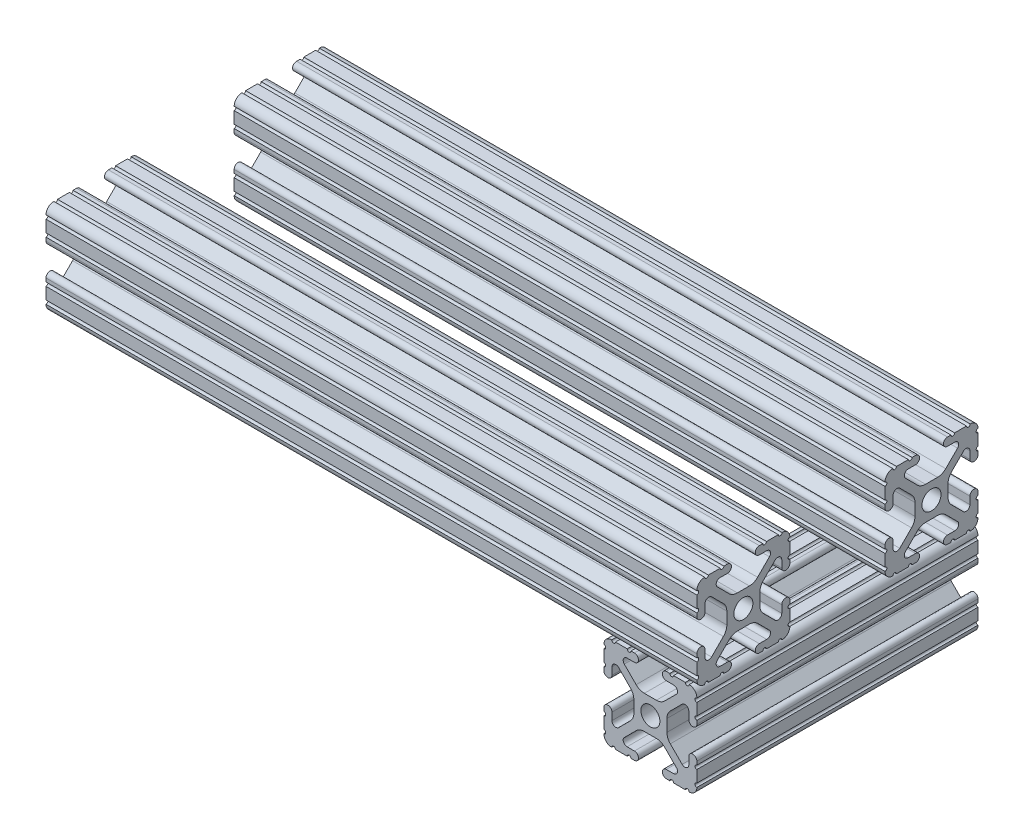
SolidWorks part; units mm, degrees
ref_plane "Front" through (0, 0, 0) normal (0, 0, 1) x (1, 0, 0)
ref_plane "Top" through (0, 0, 0) normal (0, 1, 0) x (1, 0, 0)
ref_plane "Right" through (0, 0, 0) normal (1, 0, 0) x (0, 0, -1)
sketch3d "3DSketch1"
  line L0 (0, 0, 0) -> (0, 0, 177.8)
  line L6 (51.4, 0, 0) -> (51.4, 0, 177.8)
  line L9 (64.1, 0, 12.7) -> (-12.7, 0, 12.7) construction
  line L10 (64.1, 0, 12.7) -> (64.1, -92.288, 12.7) construction
  line L13 (-12.7, 0, 12.7) -> (-12.7, -92.288, 12.7) construction
  line L15 (64.1, -25.4, 12.7) -> (-12.7, -25.4, 12.7)
  line L16 (-31.9313, 0, 139.7) -> (64.1, 0, 139.7) construction
  line L17 (-31.9313, 0, 139.7) -> (-31.9312, -88.6465, 139.7) construction
  line L18 (64.1, 0, 139.7) -> (64.1, -88.6465, 139.7) construction
  dimension "D3" = 177.8
  dimension "D2" = 51.4
  dimension "D4" = 177.8
  dimension "D5" = 38.1
  dimension "D6" = 12.7
  dimension "D12" = 25.4
  dimension "D7" = 12.7
  dimension "D8" = 12.7
  dimension "D9" = 12.7
  dimension "D14" = 31.9313
other "8020 1010(1)"
ref_plane "Plane1" through (0, 0, 0) normal (0, 0, 1) x (1, 0, 0)
sketch "Sketch1" plane through (0, 0, 0) normal (0, 0, 1) x (1, 0, 0)
  line L0 (10.5918, 12.7) -> (10.5664, 12.7)
  line L1 (9.5504, 12.7) -> (6.3246, 12.7)
  line L2 (5.3086, 12.7) -> (4.3561, 12.7)
  line L3 (4.3561, 10.4902) -> (6.3701, 10.4902)
  line L4 (7.1192, 8.6817) -> (3.8846, 5.4471)
  line L5 (1.6396, 4.5172) -> (-1.6396, 4.5172)
  line L6 (-3.8846, 5.4471) -> (-7.1192, 8.6817)
  line L7 (-6.3701, 10.4902) -> (-4.3561, 10.4902)
  line L8 (-4.3561, 12.7) -> (-5.3086, 12.7)
  line L9 (-6.3246, 12.7) -> (-9.5504, 12.7)
  line L10 (-10.5664, 12.7) -> (-10.5918, 12.7)
  line L11 (-12.7, 10.5918) -> (-12.7, 10.5664)
  line L12 (-12.7, 9.5504) -> (-12.7, 6.3246)
  line L13 (-12.7, 5.3086) -> (-12.7, 4.3561)
  line L14 (-10.4902, 4.3561) -> (-10.4902, 6.3701)
  line L15 (-8.6817, 7.1192) -> (-5.4471, 3.8846)
  line L16 (-4.5172, 1.6396) -> (-4.5172, -1.6396)
  line L17 (-5.4471, -3.8846) -> (-8.6817, -7.1192)
  line L18 (-10.4902, -6.3701) -> (-10.4902, -4.3561)
  line L19 (-12.7, -4.3561) -> (-12.7, -5.3086)
  line L20 (-12.7, -6.3246) -> (-12.7, -9.5504)
  line L21 (-12.7, -10.5664) -> (-12.7, -10.5918)
  line L22 (-10.5918, -12.7) -> (-10.5664, -12.7)
  line L23 (-9.5504, -12.7) -> (-6.3246, -12.7)
  line L24 (-5.3086, -12.7) -> (-4.3561, -12.7)
  line L25 (-4.3561, -10.4902) -> (-6.3701, -10.4902)
  line L26 (-7.1192, -8.6817) -> (-3.8846, -5.4471)
  line L27 (-1.6396, -4.5172) -> (1.6396, -4.5172)
  line L28 (3.8846, -5.4471) -> (7.1192, -8.6817)
  line L29 (6.3701, -10.4902) -> (4.3561, -10.4902)
  line L30 (4.3561, -12.7) -> (5.3086, -12.7)
  line L31 (6.3246, -12.7) -> (9.5504, -12.7)
  line L32 (10.5664, -12.7) -> (10.5918, -12.7)
  line L33 (12.7, -10.5918) -> (12.7, -10.5664)
  line L34 (12.7, -9.5504) -> (12.7, -6.3246)
  line L35 (12.7, -5.3086) -> (12.7, -4.3561)
  line L36 (10.4902, -4.3561) -> (10.4902, -6.3701)
  line L37 (8.6817, -7.1192) -> (5.4471, -3.8846)
  line L38 (4.5172, -1.6396) -> (4.5172, 1.6396)
  line L39 (5.4471, 3.8846) -> (8.6817, 7.1192)
  line L40 (10.4902, 6.3701) -> (10.4902, 4.3561)
  line L41 (12.7, 4.3561) -> (12.7, 5.3086)
  line L42 (12.7, 6.3246) -> (12.7, 9.5504)
  line L43 (12.7, 10.5664) -> (12.7, 10.5918)
  circle A0 centre (0, 0) radius 2.6035
  arc A1 (12.7, 10.5918) -> (10.5918, 12.7) centre (10.5918, 10.5918) ccw
  arc A2 (9.5504, 12.7) -> (10.5664, 12.7) centre (10.0584, 12.7) ccw
  arc A3 (5.3086, 12.7) -> (6.3246, 12.7) centre (5.8166, 12.7) ccw
  arc A4 (4.3561, 12.7) -> (4.3561, 10.4902) centre (4.3561, 11.5951) ccw
  arc A5 (7.1192, 8.6817) -> (6.3701, 10.4902) centre (6.3701, 9.4308) ccw
  arc A6 (1.6396, 4.5172) -> (3.8846, 5.4471) centre (1.6396, 7.6922) ccw
  arc A7 (-3.8846, 5.4471) -> (-1.6396, 4.5172) centre (-1.6396, 7.6922) ccw
  arc A8 (-6.3701, 10.4902) -> (-7.1192, 8.6817) centre (-6.3701, 9.4308) ccw
  arc A9 (-4.3561, 10.4902) -> (-4.3561, 12.7) centre (-4.3561, 11.5951) ccw
  arc A10 (-6.3246, 12.7) -> (-5.3086, 12.7) centre (-5.8166, 12.7) ccw
  arc A11 (-10.5664, 12.7) -> (-9.5504, 12.7) centre (-10.0584, 12.7) ccw
  arc A12 (-10.5918, 12.7) -> (-12.7, 10.5918) centre (-10.5918, 10.5918) ccw
  arc A13 (-12.7, 9.5504) -> (-12.7, 10.5664) centre (-12.7, 10.0584) ccw
  arc A14 (-12.7, 5.3086) -> (-12.7, 6.3246) centre (-12.7, 5.8166) ccw
  arc A15 (-12.7, 4.3561) -> (-10.4902, 4.3561) centre (-11.5951, 4.3561) ccw
  arc A16 (-8.6817, 7.1192) -> (-10.4902, 6.3701) centre (-9.4308, 6.3701) ccw
  arc A17 (-4.5172, 1.6396) -> (-5.4471, 3.8846) centre (-7.6922, 1.6396) ccw
  arc A18 (-5.4471, -3.8846) -> (-4.5172, -1.6396) centre (-7.6922, -1.6396) ccw
  arc A19 (-10.4902, -6.3701) -> (-8.6817, -7.1192) centre (-9.4308, -6.3701) ccw
  arc A20 (-10.4902, -4.3561) -> (-12.7, -4.3561) centre (-11.5951, -4.3561) ccw
  arc A21 (-12.7, -6.3246) -> (-12.7, -5.3086) centre (-12.7, -5.8166) ccw
  arc A22 (-12.7, -10.5664) -> (-12.7, -9.5504) centre (-12.7, -10.0584) ccw
  arc A23 (-12.7, -10.5918) -> (-10.5918, -12.7) centre (-10.5918, -10.5918) ccw
  arc A24 (-9.5504, -12.7) -> (-10.5664, -12.7) centre (-10.0584, -12.7) ccw
  arc A25 (-5.3086, -12.7) -> (-6.3246, -12.7) centre (-5.8166, -12.7) ccw
  arc A26 (-4.3561, -12.7) -> (-4.3561, -10.4902) centre (-4.3561, -11.5951) ccw
  arc A27 (-7.1192, -8.6817) -> (-6.3701, -10.4902) centre (-6.3701, -9.4308) ccw
  arc A28 (-1.6396, -4.5172) -> (-3.8846, -5.4471) centre (-1.6396, -7.6922) ccw
  arc A29 (3.8846, -5.4471) -> (1.6396, -4.5172) centre (1.6396, -7.6922) ccw
  arc A30 (6.3701, -10.4902) -> (7.1192, -8.6817) centre (6.3701, -9.4308) ccw
  arc A31 (4.3561, -10.4902) -> (4.3561, -12.7) centre (4.3561, -11.5951) ccw
  arc A32 (6.3246, -12.7) -> (5.3086, -12.7) centre (5.8166, -12.7) ccw
  arc A33 (10.5664, -12.7) -> (9.5504, -12.7) centre (10.0584, -12.7) ccw
  arc A34 (10.5918, -12.7) -> (12.7, -10.5918) centre (10.5918, -10.5918) ccw
  arc A35 (12.7, -9.5504) -> (12.7, -10.5664) centre (12.7, -10.0584) ccw
  arc A36 (12.7, -5.3086) -> (12.7, -6.3246) centre (12.7, -5.8166) ccw
  arc A37 (12.7, -4.3561) -> (10.4902, -4.3561) centre (11.5951, -4.3561) ccw
  arc A38 (8.6817, -7.1192) -> (10.4902, -6.3701) centre (9.4308, -6.3701) ccw
  arc A39 (4.5172, -1.6396) -> (5.4471, -3.8846) centre (7.6922, -1.6396) ccw
  arc A40 (5.4471, 3.8846) -> (4.5172, 1.6396) centre (7.6922, 1.6396) ccw
  arc A41 (10.4902, 6.3701) -> (8.6817, 7.1192) centre (9.4308, 6.3701) ccw
  arc A42 (10.4902, 4.3561) -> (12.7, 4.3561) centre (11.5951, 4.3561) ccw
  arc A43 (12.7, 6.3246) -> (12.7, 5.3086) centre (12.7, 5.8166) ccw
  arc A44 (12.7, 10.5664) -> (12.7, 9.5504) centre (12.7, 10.0584) ccw
  point P0 (0, 0)
other "8020 1010(2)"
ref_plane "Plane2" through (64.1, -25.4, 12.7) normal (-1, 0, 0) x (0, 1, 0)
sketch "Sketch13" plane through (64.1, -25.4, 12.7) normal (-1, 0, 0) x (0, 1, 0)
  line L0 (10.5918, 12.7) -> (10.5664, 12.7)
  line L1 (9.5504, 12.7) -> (6.3246, 12.7)
  line L2 (5.3086, 12.7) -> (4.3561, 12.7)
  line L3 (4.3561, 10.4902) -> (6.3701, 10.4902)
  line L4 (7.1192, 8.6817) -> (3.8846, 5.4471)
  line L5 (1.6396, 4.5172) -> (-1.6396, 4.5172)
  line L6 (-3.8846, 5.4471) -> (-7.1192, 8.6817)
  line L7 (-6.3701, 10.4902) -> (-4.3561, 10.4902)
  line L8 (-4.3561, 12.7) -> (-5.3086, 12.7)
  line L9 (-6.3246, 12.7) -> (-9.5504, 12.7)
  line L10 (-10.5664, 12.7) -> (-10.5918, 12.7)
  line L11 (-12.7, 10.5918) -> (-12.7, 10.5664)
  line L12 (-12.7, 9.5504) -> (-12.7, 6.3246)
  line L13 (-12.7, 5.3086) -> (-12.7, 4.3561)
  line L14 (-10.4902, 4.3561) -> (-10.4902, 6.3701)
  line L15 (-8.6817, 7.1192) -> (-5.4471, 3.8846)
  line L16 (-4.5172, 1.6396) -> (-4.5172, -1.6396)
  line L17 (-5.4471, -3.8846) -> (-8.6817, -7.1192)
  line L18 (-10.4902, -6.3701) -> (-10.4902, -4.3561)
  line L19 (-12.7, -4.3561) -> (-12.7, -5.3086)
  line L20 (-12.7, -6.3246) -> (-12.7, -9.5504)
  line L21 (-12.7, -10.5664) -> (-12.7, -10.5918)
  line L22 (-10.5918, -12.7) -> (-10.5664, -12.7)
  line L23 (-9.5504, -12.7) -> (-6.3246, -12.7)
  line L24 (-5.3086, -12.7) -> (-4.3561, -12.7)
  line L25 (-4.3561, -10.4902) -> (-6.3701, -10.4902)
  line L26 (-7.1192, -8.6817) -> (-3.8846, -5.4471)
  line L27 (-1.6396, -4.5172) -> (1.6396, -4.5172)
  line L28 (3.8846, -5.4471) -> (7.1192, -8.6817)
  line L29 (6.3701, -10.4902) -> (4.3561, -10.4902)
  line L30 (4.3561, -12.7) -> (5.3086, -12.7)
  line L31 (6.3246, -12.7) -> (9.5504, -12.7)
  line L32 (10.5664, -12.7) -> (10.5918, -12.7)
  line L33 (12.7, -10.5918) -> (12.7, -10.5664)
  line L34 (12.7, -9.5504) -> (12.7, -6.3246)
  line L35 (12.7, -5.3086) -> (12.7, -4.3561)
  line L36 (10.4902, -4.3561) -> (10.4902, -6.3701)
  line L37 (8.6817, -7.1192) -> (5.4471, -3.8846)
  line L38 (4.5172, -1.6396) -> (4.5172, 1.6396)
  line L39 (5.4471, 3.8846) -> (8.6817, 7.1192)
  line L40 (10.4902, 6.3701) -> (10.4902, 4.3561)
  line L41 (12.7, 4.3561) -> (12.7, 5.3086)
  line L42 (12.7, 6.3246) -> (12.7, 9.5504)
  line L43 (12.7, 10.5664) -> (12.7, 10.5918)
  circle A0 centre (0, 0) radius 2.6035
  arc A1 (12.7, 10.5918) -> (10.5918, 12.7) centre (10.5918, 10.5918) ccw
  arc A2 (9.5504, 12.7) -> (10.5664, 12.7) centre (10.0584, 12.7) ccw
  arc A3 (5.3086, 12.7) -> (6.3246, 12.7) centre (5.8166, 12.7) ccw
  arc A4 (4.3561, 12.7) -> (4.3561, 10.4902) centre (4.3561, 11.5951) ccw
  arc A5 (7.1192, 8.6817) -> (6.3701, 10.4902) centre (6.3701, 9.4308) ccw
  arc A6 (1.6396, 4.5172) -> (3.8846, 5.4471) centre (1.6396, 7.6922) ccw
  arc A7 (-3.8846, 5.4471) -> (-1.6396, 4.5172) centre (-1.6396, 7.6922) ccw
  arc A8 (-6.3701, 10.4902) -> (-7.1192, 8.6817) centre (-6.3701, 9.4308) ccw
  arc A9 (-4.3561, 10.4902) -> (-4.3561, 12.7) centre (-4.3561, 11.5951) ccw
  arc A10 (-6.3246, 12.7) -> (-5.3086, 12.7) centre (-5.8166, 12.7) ccw
  arc A11 (-10.5664, 12.7) -> (-9.5504, 12.7) centre (-10.0584, 12.7) ccw
  arc A12 (-10.5918, 12.7) -> (-12.7, 10.5918) centre (-10.5918, 10.5918) ccw
  arc A13 (-12.7, 9.5504) -> (-12.7, 10.5664) centre (-12.7, 10.0584) ccw
  arc A14 (-12.7, 5.3086) -> (-12.7, 6.3246) centre (-12.7, 5.8166) ccw
  arc A15 (-12.7, 4.3561) -> (-10.4902, 4.3561) centre (-11.5951, 4.3561) ccw
  arc A16 (-8.6817, 7.1192) -> (-10.4902, 6.3701) centre (-9.4308, 6.3701) ccw
  arc A17 (-4.5172, 1.6396) -> (-5.4471, 3.8846) centre (-7.6922, 1.6396) ccw
  arc A18 (-5.4471, -3.8846) -> (-4.5172, -1.6396) centre (-7.6922, -1.6396) ccw
  arc A19 (-10.4902, -6.3701) -> (-8.6817, -7.1192) centre (-9.4308, -6.3701) ccw
  arc A20 (-10.4902, -4.3561) -> (-12.7, -4.3561) centre (-11.5951, -4.3561) ccw
  arc A21 (-12.7, -6.3246) -> (-12.7, -5.3086) centre (-12.7, -5.8166) ccw
  arc A22 (-12.7, -10.5664) -> (-12.7, -9.5504) centre (-12.7, -10.0584) ccw
  arc A23 (-12.7, -10.5918) -> (-10.5918, -12.7) centre (-10.5918, -10.5918) ccw
  arc A24 (-9.5504, -12.7) -> (-10.5664, -12.7) centre (-10.0584, -12.7) ccw
  arc A25 (-5.3086, -12.7) -> (-6.3246, -12.7) centre (-5.8166, -12.7) ccw
  arc A26 (-4.3561, -12.7) -> (-4.3561, -10.4902) centre (-4.3561, -11.5951) ccw
  arc A27 (-7.1192, -8.6817) -> (-6.3701, -10.4902) centre (-6.3701, -9.4308) ccw
  arc A28 (-1.6396, -4.5172) -> (-3.8846, -5.4471) centre (-1.6396, -7.6922) ccw
  arc A29 (3.8846, -5.4471) -> (1.6396, -4.5172) centre (1.6396, -7.6922) ccw
  arc A30 (6.3701, -10.4902) -> (7.1192, -8.6817) centre (6.3701, -9.4308) ccw
  arc A31 (4.3561, -10.4902) -> (4.3561, -12.7) centre (4.3561, -11.5951) ccw
  arc A32 (6.3246, -12.7) -> (5.3086, -12.7) centre (5.8166, -12.7) ccw
  arc A33 (10.5664, -12.7) -> (9.5504, -12.7) centre (10.0584, -12.7) ccw
  arc A34 (10.5918, -12.7) -> (12.7, -10.5918) centre (10.5918, -10.5918) ccw
  arc A35 (12.7, -9.5504) -> (12.7, -10.5664) centre (12.7, -10.0584) ccw
  arc A36 (12.7, -5.3086) -> (12.7, -6.3246) centre (12.7, -5.8166) ccw
  arc A37 (12.7, -4.3561) -> (10.4902, -4.3561) centre (11.5951, -4.3561) ccw
  arc A38 (8.6817, -7.1192) -> (10.4902, -6.3701) centre (9.4308, -6.3701) ccw
  arc A39 (4.5172, -1.6396) -> (5.4471, -3.8846) centre (7.6922, -1.6396) ccw
  arc A40 (5.4471, 3.8846) -> (4.5172, 1.6396) centre (7.6922, 1.6396) ccw
  arc A41 (10.4902, 6.3701) -> (8.6817, 7.1192) centre (9.4308, 6.3701) ccw
  arc A42 (10.4902, 4.3561) -> (12.7, 4.3561) centre (11.5951, 4.3561) ccw
  arc A43 (12.7, 6.3246) -> (12.7, 5.3086) centre (12.7, 5.8166) ccw
  arc A44 (12.7, 10.5664) -> (12.7, 9.5504) centre (12.7, 10.0584) ccw
  point P0 (0, 0)
move or copy body "Body-Move/Copy2" bodies to move or copy 102 101 151 copy no rotation origin (23.2961, 0, 82.55) rotation axis (0, -1, 0) rotation angle 90
